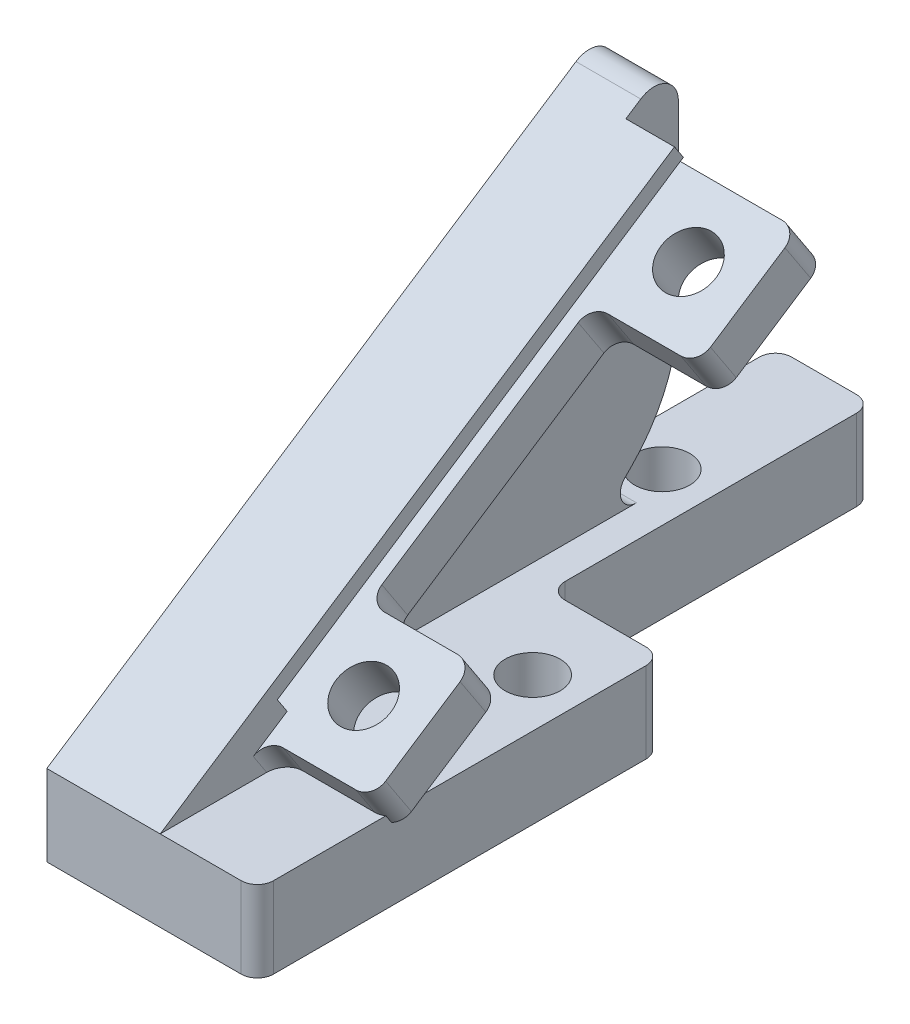
SolidWorks part; units mm, degrees
ref_plane "前视基准面" through (0, 0, 0) normal (0, 0, 1) x (1, 0, 0)
ref_plane "上视基准面" through (0, 0, 0) normal (0, 1, 0) x (1, 0, 0)
ref_plane "右视基准面" through (0, 0, 0) normal (1, 0, 0) x (0, 0, -1)
other "Configuration Table"
sketch "草图1" plane through (0, 0, 0) normal (0, 1, 0) x (1, 0, 0)
  line L0 (0, 0) -> (0, 44)
  line L1 (1, 45) -> (5, 45)
  line L2 (6, 44) -> (6, 26)
  line L3 (7, 25) -> (12, 25)
  line L4 (13, 24) -> (13, 1)
  line L5 (12, 0) -> (0, 0)
  arc A0 (0, 44) -> (1, 45) centre (1, 44) cw
  arc A1 (5, 45) -> (6, 44) centre (5, 44) cw
  arc A2 (6, 26) -> (7, 25) centre (7, 26) ccw
  arc A3 (12, 25) -> (13, 24) centre (12, 24) cw
  arc A5 (13, 1) -> (12, 0) centre (12, 1) cw
  point P9 (0, 45)
  point P12 (6, 45)
  point P15 (6, 25)
  point P18 (13, 25)
  point P21 (0, 0)
  point P24 (13, 0)
  dimension "D5" = 1
  dimension "D6" = 1
  dimension "D7" = 1
  dimension "D8" = 1
  dimension "D10" = 1
  dimension "D1" = 13
  dimension "D2" = 25
  dimension "D3" = 20
  dimension "D4" = 6
extrude "凸台-拉伸1" add sketch "草图1" along normal blind 5 contours L5 L0 A0 L1 A1 L2 A2 L3 A3 L4 A5
sketch "草图3" plane through (0, 0, 0) normal (1, 0, 0) x (0, 0, -1)
  line L4 (1, 5) -> (0, 5) construction
  line L5 (0, 7.15) -> (0, -7.15) construction
  line L6 (30, 5) -> (0, 5)
  line L7 (30, 5) -> (32.0711, 7.0711)
  line L9 (35, 14.1421) -> (35, 25.2107)
  line L10 (0, 5) -> (32.6765, 26.4644)
  line L12 (44, 5) -> (26, 5) construction
  arc A2 (32.0711, 7.0711) -> (35, 14.1421) centre (25, 14.1421) ccw
  arc A3 (35, 25.2107) -> (32.6765, 26.4644) centre (33.5, 25.2107) ccw
  point P5 (0, 0)
  dimension "D5" = 10
  dimension "D1" = 33.3
  dimension "D3" = 1.5
  dimension "D2" = 35
  dimension "D6" = 30
  dimension "D7" = 45
extrude "凸台-拉伸3" add sketch "草图3" along normal blind 4
sketch "草图4" plane through (4, 0, 0) normal (1, 0, 0) x (0, 0, -1)
  line L0 (0, 5) -> (31.7607, 25.8629)
  line L5 (30, 5) -> (0, 5) construction
  line L7 (34.5058, 21.6838) -> (9.1071, 5)
  line L12 (31.7607, 25.8629) -> (34.5058, 21.6838)
  line L14 (0, 5) -> (9.1071, 5)
  line L15 (24, 5) -> (1, 5) construction
  line L17 (0, 5) -> (30, 5) construction
  line L18 (32.6765, 26.4644) -> (0, 5) construction
  point P4 (-61.995, 10.579)
  dimension "D1" = 5
  dimension "D2" = 38
  dimension "D3" = 33.3
extrude "凸台-拉伸4" add sketch "草图4" along normal blind 3
sketch "草图5" plane through (7, 0, 0) normal (1, 0, 0) x (0, 0, -1)
  line L0 (32.6117, 24.5674) -> (7.5374, 8.0967)
  line L1 (34.5058, 21.6838) -> (31.7607, 25.8629) construction
  line L3 (31.7607, 25.8629) -> (0, 5) construction
  dimension "D1" = 1.55
  dimension "D2" = 30
extrude "切除-拉伸-薄壁1" cut sketch "草图5" against normal blind 2 thin thin type mid plane wall 1.1
sketch "草图6" plane through (0, 0, 0) normal (0, -1, 0) x (1, 0, 0)
  circle A0 centre (3, -5) radius 1.7
  circle A1 centre (3, -35) radius 1.7
  circle A2 centre (10, -20) radius 1.7
extrude "切除-拉伸1" cut sketch "草图6" against normal blind 5.5
ref_plane "基准面2" through (0, 0, 0) normal (1, 0, 0) x (0, 0, -1)
sketch "草图7" plane through (7, 0, 0) normal (1, 0, 0) x (0, 0, -1)
  line L0 (32.9136, 24.1077) -> (34.5058, 21.6838)
  line L1 (34.5058, 21.6838) -> (28.2372, 17.5662)
  line L2 (9.1071, 5) -> (34.5058, 21.6838) construction
  line L3 (28.2372, 17.5662) -> (26.6451, 19.99)
  line L4 (32.9136, 24.1077) -> (7.8394, 7.637) construction
  line L5 (26.6451, 19.99) -> (32.9136, 24.1077)
  dimension "D2" = 7.5
extrude "凸台-拉伸5" add sketch "草图7" along normal blind 6.5
fillet "圆角1" radius 1 2 edges at (13.5, 18.7781, -27.4412) (13.5, 22.8958, -33.7097)
sketch "草图8" plane through (0, 1.7377, 1.1414) normal (0, 0.8358, 0.549) x (1, 0, 0)
  line L0 (13.5, 39.7451) -> (13.5, 34.2451) construction
  line L1 (5, 40.7451) -> (12.5, 40.7451) construction
  circle A0 centre (9.8, 37.0451) radius 1.7
  dimension "D1" = 3.7
  dimension "D2" = 3.7
extrude "切除-拉伸2" cut sketch "草图8" against normal up to next
fillet "圆角2" radius 1 1 edges at (7, 18.7781, -27.4412)
pattern_linear "阵列(线性)2" count 2 spacing 24 along (0, -0.549, 0.8358) of "凸台-拉伸5", "圆角1", "切除-拉伸2", "圆角2"
fillet "圆角3" radius 1 1 edges at (7, 9.7192, -13.6503)
fillet "圆角4" radius 1 1 edges at (2, 5, -30)
